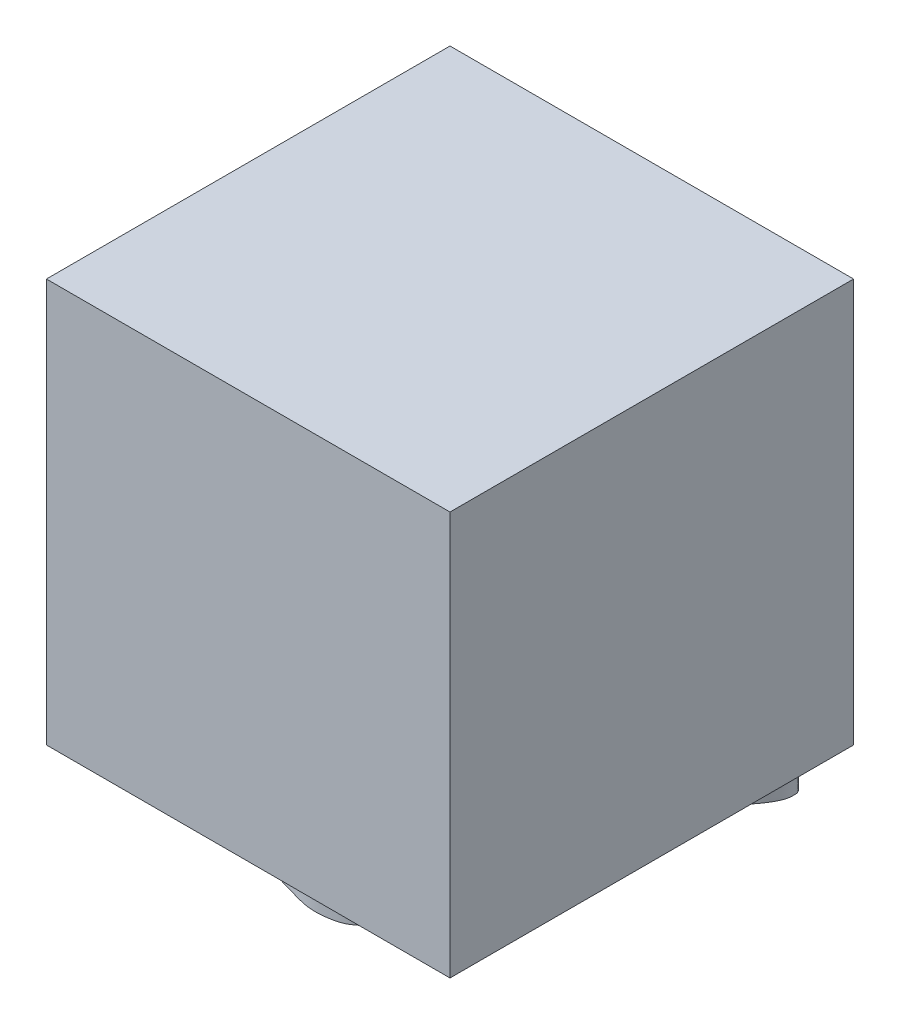
SolidWorks part; units mm, degrees
ref_plane "前视基准面" through (0, 0, 0) normal (0, 0, 1) x (1, 0, 0)
ref_plane "上视基准面" through (0, 0, 0) normal (0, 1, 0) x (1, 0, 0)
ref_plane "右视基准面" through (0, 0, 0) normal (1, 0, 0) x (0, 0, -1)
other "Configuration Table"
sketch "草图1" plane through (0, 0, 0) normal (0, 1, 0) x (1, 0, 0)
  line L1 (-15, -15) -> (15, -15)
  line L2 (-15, -15) -> (-15, 15)
  line L3 (-15, 15) -> (15, 15)
  line L4 (15, -15) -> (15, 15)
  line L5 (-15, -15) -> (15, 15) construction
  line L6 (-15, 15) -> (15, -15) construction
  point P0 (0, 0)
  dimension "D1" = 30
  dimension "D2" = 30
extrude "凸台-拉伸1" add sketch "草图1" along normal blind 30
sketch "草图2" plane through (0, 0, 0) normal (0, -1, 0) x (1, 0, 0)
  line L0 (33.1314, 126.5852) -> (221.1314, 126.5852) construction
  spline S0 degree 3 poles (0.3695, 13.0041) (-0.5736, 12.5981) (-1.7752, 11.9689) (-3.6176, 11.6207) (-5.4299, 11.0714) (-6.7179, 10.8525) (-7.5358, 11.0254) (-7.9249, 10.4005) (-7.4773, 9.7062) (-7.3847, 8.8437) (-6.874, 7.8699) (-7.1603, 6.8755) (-7.294, 5.7042) (-7.4213, 4.2642) (-7.7075, 2.0623) (-8.4642, -1.2168) (-9.4163, -4.9642) (-11.1752, -8.9558) (-12.2775, -11.4072) (-14.0501, -12.485) (-13.933, -12.7798) (-13.7446, -12.9725) (-13.3937, -12.9864) (-12.8737, -12.8996) (-12.1166, -12.8609) (-11.4523, -12.2446) (-10.3147, -11.5956) (-9.2991, -10.1562) (-7.9869, -8.0158) (-6.573, -5.2581) (-5.831, -2.1273) (-5.0219, 0.0043) (-4.9337, 1.0593) (-4.8267, 1.3236) (-4.5984, 1.4372) (-4.2883, 1.4116) (-3.9434, 1.3245) (-3.423, 1.1803) (-3.246, 0.4127) (-3.3279, -0.3009) (-3.3566, -1.2565) (-3.3326, -2.5519) (-3.6027, -4.207) (-3.8401, -5.835) (-4.2193, -7.4126) (-4.2423, -8.9159) (-4.3691, -10.6416) (-3.6519, -11.9902) (-2.8098, -12.9696) (-1.8096, -13.6374) (-0.4962, -14.0171) (0.5675, -13.3703) (1.6281, -12.9255) (1.4677, -11.8265) (2.2746, -11.2316) (2.7719, -10.3681) (3.4477, -9.5385) (3.9826, -8.5022) (4.5189, -7.5512) (4.6936, -6.8522) (5.0438, -6.2966) (5.4372, -6.7555) (5.7843, -7.1597) (6.6471, -7.855) (7.8296, -8.7642) (9.3594, -9.8625) (11.0282, -10.9269) (12.3882, -11.6972) (13.3653, -12.1782) (13.9768, -12.0542) (14.041, -11.4391) (13.9155, -10.7895) (13.4861, -10.0691) (13.0189, -9.3636) (11.8359, -8.5556) (10.5661, -7.9236) (9.1001, -7.04) (8.007, -6.4713) (6.7897, -5.8805) (6.1263, -5.3611) (4.9594, -5.1927) (5.4794, -4.6638) (5.9706, -4.3246) (6.8976, -3.6739) (7.9974, -3.0274) (9.0308, -2.0094) (9.8976, -0.7333) (10.4997, 0.6892) (9.896, 1.8943) (9.0328, 2.2623) (8.0464, 2.5247) (7.0574, 2.5819) (6.2476, 2.0778) (5.7483, 1.8751) (5.152, 1.6419) (5.6339, 1.2737) (5.9752, 1.529) (6.3474, 1.5565) (6.7093, 1.6021) (7.0719, 1.3251) (7.1549, 0.7819) (7.0429, 0.3098) (6.5413, -0.4463) (5.5218, -1.076) (3.9429, -2.0895) (1.8971, -3.168) (0.8762, -3.3685) (-0.4228, -4.163) (-0.4045, -3.8771) (-0.8032, -3.8973) (-0.656, -3.5762) (-0.7149, -3.3235) (-0.6614, -3.0219) (-0.6663, -2.7244) (-0.6351, -2.3765) (-0.7032, -1.9165) (-0.5533, -1.4105) (-0.74, -0.9501) (-1.0491, -0.4332) (-1.2606, 0.14) (-1.7376, 0.6102) (-2.031, 0.8652) (-2.3735, 0.9999) (-2.3804, 1.173) (-2.3207, 1.3153) (-2.0523, 1.4516) (-1.6549, 1.4944) (-1.2386, 1.7229) (-0.7391, 1.8137) (-0.27, 2.0021) (0.2438, 2.0993) (0.8268, 2.2447) (1.6134, 2.4483) (2.619, 2.7684) (3.9831, 3.1128) (5.5948, 3.4882) (7.1228, 3.8729) (8.5046, 3.8796) (9.2525, 4.2226) (9.8666, 4.4468) (9.9199, 4.723) (9.7713, 4.9309) (9.5265, 5.0972) (9.1735, 5.4956) (8.5558, 5.5701) (7.8924, 5.8975) (6.9769, 5.8907) (6.0741, 6.1628) (5.2835, 5.7668) (4.6012, 5.762) (3.6798, 5.2849) (2.6418, 5.1287) (1.2425, 4.624) (0.0132, 4.4698) (-1.2012, 3.9535) (-2.1928, 3.768) (-3.1258, 3.3632) (-3.773, 3.1391) (-4.1216, 3.059) (-4.2593, 3.1191) (-4.3558, 3.2115) (-4.4483, 3.355) (-4.4547, 3.6677) (-4.4776, 4.0847) (-4.3643, 4.6034) (-4.3746, 5.115) (-4.2756, 5.6244) (-4.2079, 6.051) (-4.0894, 6.2928) (-4.0672, 6.4542) (-3.9614, 6.4426) (-3.7881, 6.5355) (-3.5417, 6.3854) (-3.2187, 6.4492) (-2.9108, 6.2565) (-2.4856, 6.3728) (-2.0711, 6.1883) (-1.6361, 6.2506) (-1.2008, 6.1634) (-0.6576, 6.0582) (0.0298, 6.0688) (0.7904, 6.1634) (1.7863, 6.2429) (3.2912, 6.4068) (5.5407, 6.8171) (7.6205, 7.4669) (8.6744, 8.4847) (8.776, 8.9687) (8.5895, 9.2006) (8.3511, 9.5147) (7.9169, 9.8823) (7.2948, 10.0605) (6.3989, 10.2373) (5.3413, 10.133) (3.9151, 9.9151) (2.097, 9.2546) (0.0697, 8.3827) (-1.9141, 7.9036) (-3.015, 7.5298) (-3.6914, 7.42) (-3.9518, 7.6313) (-4.0785, 7.8462) (-4.1671, 8.1598) (-4.1837, 8.5137) (-4.2113, 8.9239) (-4.2257, 9.3808) (-4.5625, 9.671) (-4.8105, 9.8796) (-4.9735, 10.0322) (-4.9473, 10.2923) (-4.6164, 10.333) (-4.2101, 10.1932) (-3.6966, 10.1061) (-3.1882, 10.0012) (-2.6635, 9.9094) (-1.6528, 9.8016) (-0.4772, 9.8964) (0.9336, 10.1403) (2.2083, 10.4914) (4.02, 10.8572) (5.4834, 11.4156) (6.469, 12.3262) (6.3877, 12.8589) (6.0359, 13.1534) (5.4952, 13.4955) (4.5025, 13.7205) (3.0555, 13.8098) (1.5942, 13.3017) (0.3695, 13.0041) (-0.5736, 12.5981) (-1.7752, 11.9689) knots -0.017652 -0.008732 -0.003222 0 0.005626 0.015695 0.026033 0.032086 0.034131 0.036853 0.039957 0.044843 0.049046 0.054701 0.058518 0.065709 0.07489 0.089626 0.112795 0.129064 0.150063 0.15216 0.15313 0.153998 0.155863 0.157613 0.161563 0.165986 0.169813 0.179892 0.18985 0.205304 0.22286 0.234937 0.236802 0.237717 0.238769 0.240098 0.241983 0.243862 0.247165 0.25146 0.254324 0.260458 0.269626 0.277709 0.283543 0.292254 0.298797 0.30735 0.312707 0.316761 0.32428 0.329823 0.33422 0.33839 0.342749 0.347146 0.352422 0.357595 0.36363 0.367028 0.368836 0.370513 0.373552 0.377178 0.385561 0.394723 0.403457 0.413297 0.416627 0.418663 0.420672 0.424201 0.428134 0.432223 0.435944 0.447939 0.452199 0.459836 0.465506 0.470215 0.473964 0.475273 0.47877 0.483108 0.490763 0.496763 0.503086 0.512856 0.515736 0.521049 0.525165 0.530277 0.534347 0.537689 0.539163 0.540904 0.542912 0.544677 0.546108 0.547867 0.550396 0.553346 0.554483 0.563033 0.569415 0.581576 0.591428 0.593424 0.593526 0.595227 0.596045 0.597437 0.598964 0.600225 0.601617 0.603838 0.606686 0.608649 0.610551 0.615192 0.616985 0.619774 0.620956 0.62138 0.62205 0.623015 0.625369 0.627647 0.629532 0.632442 0.634693 0.636841 0.640862 0.646073 0.65162 0.660565 0.66926 0.673692 0.679504 0.681145 0.68204 0.682985 0.684524 0.686218 0.69024 0.69269 0.696496 0.702923 0.704935 0.708583 0.712218 0.719227 0.723148 0.733024 0.736362 0.741561 0.747078 0.750496 0.751276 0.751943 0.752491 0.753145 0.75427 0.756748 0.75903 0.761636 0.763861 0.76634 0.767486 0.767849 0.768292 0.768684 0.770594 0.771616 0.773173 0.775279 0.777369 0.779258 0.78129 0.783551 0.787005 0.790847 0.794299 0.800999 0.812024 0.826485 0.830625 0.83184 0.832854 0.834571 0.837478 0.840564 0.843522 0.850248 0.855243 0.863745 0.877182 0.88623 0.892016 0.893906 0.895213 0.896408 0.897378 0.899745 0.901327 0.903206 0.905863 0.907049 0.907842 0.908906 0.909808 0.911922 0.915087 0.917012 0.919212 0.922543 0.931229 0.935603 0.942595 0.94976 0.961326 0.965075 0.966426 0.968311 0.971221 0.975413 0.982348 0.991268 0.996778 1 1.005626 1.015695 1.026033 only from (-0.4131, 12.6602) to (-0.4131, 12.6602)
  spline S1 degree 3 poles (-0.7356, -4.5008) (-0.6528, -4.9011) (-0.8703, -5.395) (-1.0907, -6.1032) (-1.1831, -6.8872) (-1.4227, -7.5253) (-1.6187, -8.3334) (-1.7339, -9.0905) (-1.8291, -9.8915) (-1.3856, -10.2122) (-0.9322, -10.1851) (-0.3802, -9.8636) (0.2818, -9.3383) (1.1725, -8.7678) (1.9484, -7.9589) (2.7954, -7.1236) (3.3306, -6.4474) (4.0587, -5.7776) (3.6814, -5.4647) (3.2882, -5.0933) (2.5585, -4.929) (1.6496, -4.7671) (0.8368, -4.7749) (0.07, -4.6428) (-0.3245, -4.5714) (-0.7356, -4.5008) (-0.6528, -4.9011) (-0.8703, -5.395) knots -0.04819 -0.024621 -0.008811 0 0.031861 0.085166 0.122786 0.16453 0.199659 0.261557 0.3005 0.319029 0.34586 0.371948 0.425743 0.488581 0.548726 0.615854 0.680888 0.720206 0.7316 0.755652 0.813704 0.8505 0.912215 0.95181 0.975379 0.991189 1 1.031861 1.085166 1.122786 only from (-0.6938, -4.7342) to (-0.6938, -4.7342)
extrude "凸台-拉伸2" add sketch "草图2" along normal blind 2
